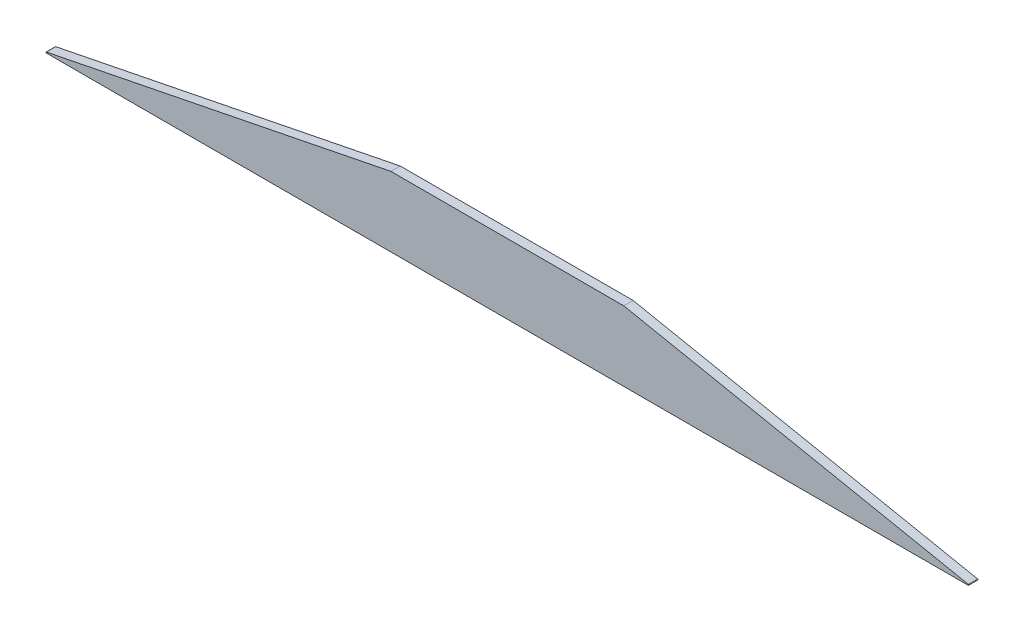
SolidWorks part; units mm, degrees
ref_plane "Front Plane" through (0, 0, 0) normal (0, 0, 1) x (1, 0, 0)
ref_plane "Top Plane" through (0, 0, 0) normal (0, 1, 0) x (1, 0, 0)
ref_plane "Right Plane" through (0, 0, 0) normal (1, 0, 0) x (0, 0, -1)
sketch "Sketch1" plane through (0, 0, 0) normal (0, 0, 1) x (1, 0, 0)
  line L0 (-500, 0) -> (500, 0)
  line L1 (55, 0) -> (-55, 0) construction
  line L2 (500, 0) -> (125, 75)
  line L3 (125, 75) -> (-125, 75)
  line L4 (-125, 75) -> (-500, 0)
  line L5 (0, -55) -> (0, 55) construction
  point P5 (0, 0)
  point P10 (248.7937, 52.3401)
  point P11 (-207.8023, 48.5872)
  point P12 (0, 75)
  dimension "D1" = 1000
  dimension "D2" = 250
  dimension "D3" = 75
extrude "Boss-Extrude1" add sketch "Sketch1" along normal blind 10
fillet "Fillet1" radius 0.5 2 edges at (500, 0, 5) (-500, 0, 5)
